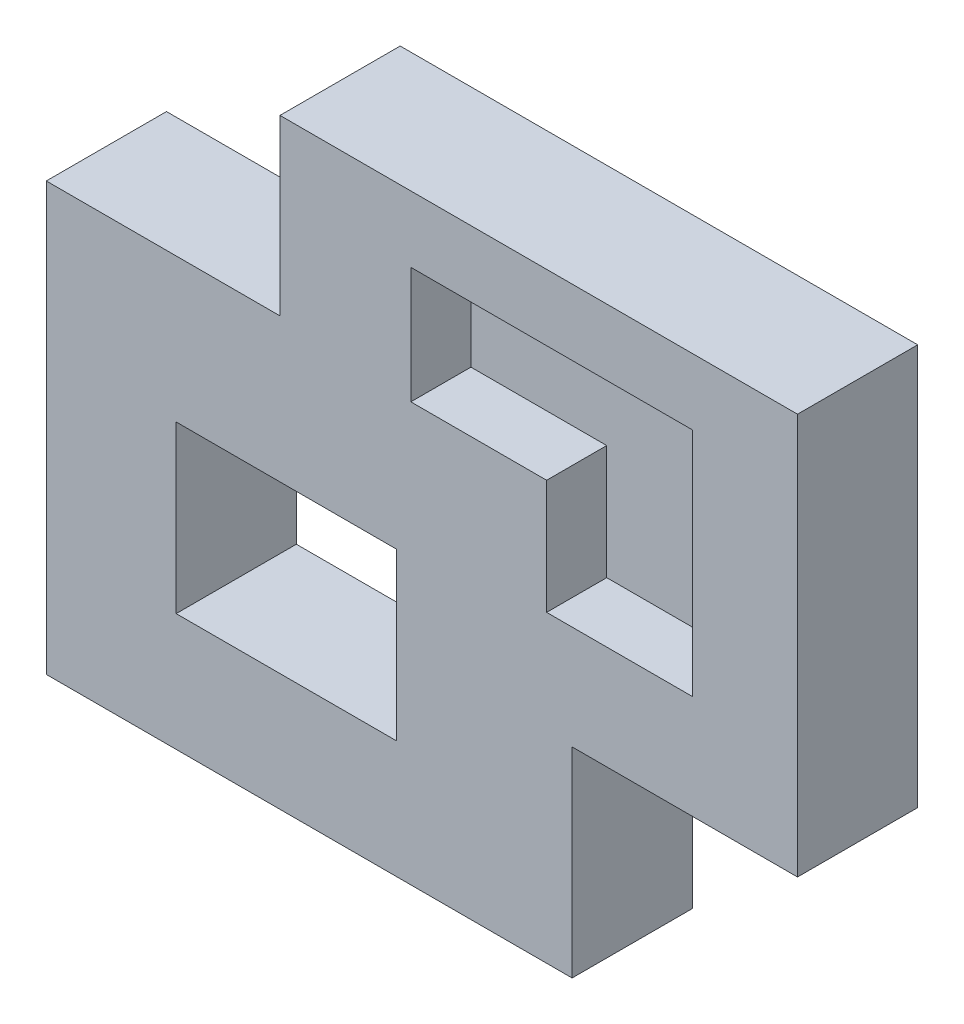
SolidWorks part; units mm, degrees
ref_plane "Front" through (0, 0, 0) normal (0, 0, 1) x (1, 0, 0)
ref_plane "Top" through (0, 0, 0) normal (0, 1, 0) x (1, 0, 0)
ref_plane "Right" through (0, 0, 0) normal (1, 0, 0) x (0, 0, -1)
sketch "Sketch1" plane through (0, 0, 0) normal (0, 0, 1) x (1, 0, 0)
  line L1 (0, 0) -> (87.4925, 0)
  line L2 (0, 0) -> (0, 71.1102)
  line L3 (38.8856, 100) -> (125, 100)
  line L4 (125, 33.3048) -> (125, 100)
  line L7 (125, 33.3048) -> (87.4925, 33.3048)
  line L8 (87.4925, 0) -> (87.4925, 33.3048)
  line L11 (0, 71.1102) -> (38.8856, 71.1102)
  line L12 (38.8856, 100) -> (38.8856, 71.1102)
extrude "Extrude1" add sketch "Sketch1" along normal blind 20
sketch "Sketch2" plane through (0, 0, 20) normal (0, 0, 1) x (1, 0, 0)
  line L1 (21.6092, 47.1853) -> (58.2953, 47.1853)
  line L2 (21.6092, 47.1853) -> (21.6092, 19.5658)
  line L3 (21.6092, 19.5658) -> (58.2953, 19.5658)
  line L4 (58.2953, 47.1853) -> (58.2953, 19.5658)
extrude "Cut-Extrude1" cut sketch "Sketch2" against normal blind 20
sketch "Sketch3" plane through (0, 0, 20) normal (0, 0, 1) x (1, 0, 0)
  line L0 (60.659, 88.9953) -> (107.4886, 88.9953)
  line L1 (107.4886, 88.9953) -> (107.4886, 50.5688)
  line L2 (107.4886, 50.5688) -> (83.2532, 50.5688)
  line L3 (83.2532, 50.5688) -> (83.2532, 69.6086)
  line L4 (83.2532, 69.6086) -> (60.659, 69.6086)
  line L5 (60.659, 69.6086) -> (60.659, 88.9953)
extrude "Cut-Extrude2" cut sketch "Sketch3" against normal blind 10
sketch "Bounding Box" plane through (0, 0, 20) normal (0, 0, 1) x (1, 0, 0)
  line L1 (0, 0) -> (125, 0)
  line L2 (0, 0) -> (0, 100)
  line L3 (0, 100) -> (125, 100)
  line L4 (125, 0) -> (125, 100)
sketch "Stock" plane through (0, 0, 20) normal (0, 0, 1) x (1, 0, 0)
  line L8 (-10, -10) -> (135, -10)
  line L9 (-10, 110) -> (-10, -10)
  line L10 (135, 110) -> (-10, 110)
  line L11 (135, -10) -> (135, 110)
  line L12 (-10, -10) -> (135, -10)
  line L13 (-10, 110) -> (-10, -10)
  line L14 (135, 110) -> (-10, 110)
  line L15 (135, -10) -> (135, 110)
  dimension "D1" = 10
sketch "Outer Silhouette" plane through (0, 0, 20) normal (0, 0, 1) x (1, 0, 0)
  line L8 (0, 71.1102) -> (0, 0)
  line L9 (0, 0) -> (87.4925, 0)
  line L10 (87.4925, 0) -> (87.4925, 33.3048)
  line L11 (87.4925, 33.3048) -> (125, 33.3048)
  line L12 (125, 33.3048) -> (125, 100)
  line L13 (125, 100) -> (38.8856, 100)
  line L14 (38.8856, 100) -> (38.8856, 71.1102)
  line L15 (38.8856, 71.1102) -> (0, 71.1102)
  line L16 (0, 71.1102) -> (0, 0)
  line L17 (0, 0) -> (87.4925, 0)
  line L18 (87.4925, 0) -> (87.4925, 33.3048)
  line L19 (87.4925, 33.3048) -> (125, 33.3048)
  line L20 (125, 33.3048) -> (125, 100)
  line L21 (125, 100) -> (38.8856, 100)
  line L22 (38.8856, 100) -> (38.8856, 71.1102)
  line L23 (38.8856, 71.1102) -> (0, 71.1102)
  dimension "D1" = 0
sketch "All Silhouettes" plane through (0, 0, 20) normal (0, 0, 1) x (1, 0, 0)
  line L0 (58.2953, 19.5658) -> (58.2953, 47.1853) construction
  line L1 (58.2953, 19.5658) -> (58.2953, 47.1853)
  line L2 (58.2953, 47.1853) -> (21.6092, 47.1853) construction
  line L3 (58.2953, 47.1853) -> (21.6092, 47.1853)
  line L4 (21.6092, 47.1853) -> (21.6092, 19.5658) construction
  line L5 (21.6092, 47.1853) -> (21.6092, 19.5658)
  line L6 (21.6092, 19.5658) -> (58.2953, 19.5658) construction
  line L7 (21.6092, 19.5658) -> (58.2953, 19.5658)
  line L8 (0, 71.1102) -> (0, 0)
  line L9 (0, 0) -> (87.4925, 0)
  line L10 (87.4925, 0) -> (87.4925, 33.3048)
  line L11 (87.4925, 33.3048) -> (125, 33.3048)
  line L12 (125, 33.3048) -> (125, 100)
  line L13 (125, 100) -> (38.8856, 100)
  line L14 (38.8856, 100) -> (38.8856, 71.1102)
  line L15 (38.8856, 71.1102) -> (0, 71.1102)
  line L16 (0, 71.1102) -> (0, 0)
  line L17 (0, 0) -> (87.4925, 0)
  line L18 (87.4925, 0) -> (87.4925, 33.3048)
  line L19 (87.4925, 33.3048) -> (125, 33.3048)
  line L20 (125, 33.3048) -> (125, 100)
  line L21 (125, 100) -> (38.8856, 100)
  line L22 (38.8856, 100) -> (38.8856, 71.1102)
  line L23 (38.8856, 71.1102) -> (0, 71.1102)
  dimension "D1" = 0
